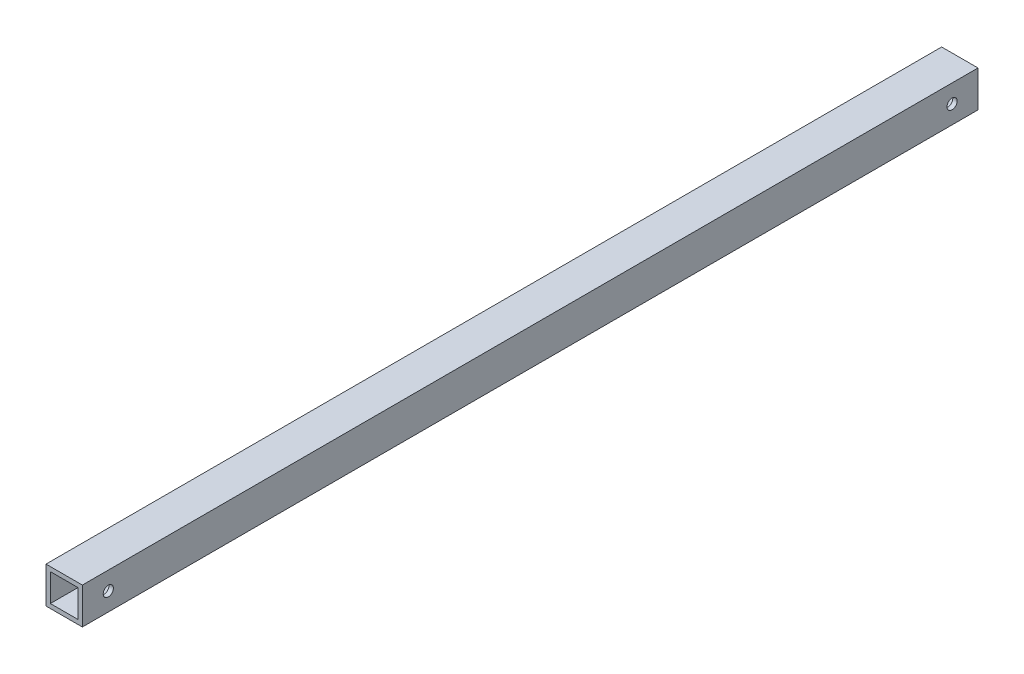
SolidWorks part; units mm, degrees
ref_plane "前视基准面" through (0, 0, 0) normal (0, 0, 1) x (1, 0, 0)
ref_plane "上视基准面" through (0, 0, 0) normal (0, 1, 0) x (1, 0, 0)
ref_plane "右视基准面" through (0, 0, 0) normal (1, 0, 0) x (0, 0, -1)
sketch "草图1" plane through (0, 0, 0) normal (0, 0, 1) x (1, 0, 0)
  line L1 (0, 0) -> (25, 0)
  line L2 (0, 0) -> (0, -25)
  line L3 (0, -25) -> (25, -25)
  line L4 (25, 0) -> (25, -25)
  line L5 (3, -3) -> (22, -3)
  line L6 (3, -3) -> (3, -22)
  line L7 (3, -22) -> (22, -22)
  line L8 (22, -3) -> (22, -22)
  dimension "D1" = 3
  dimension "D2" = 3
  dimension "D3" = 3
  dimension "D4" = 3
  dimension "D5" = 25
  dimension "D6" = 25
extrude "拉伸1" add sketch "草图1" along normal blind 616
hole_wizard "Ø7.0 (7) 直径孔1" positions "草图3" profile "草图4" hole size "Ø7.0" standard "GB" end condition through all
sketch "草图3" plane through (25, 0, 0) normal (1, 0, 0) x (0, 0, -1)
  line L0 (-616, -25) -> (-616, 0) construction
  line L1 (-616, -25) -> (0, -25) construction
  point P1 (-598.15, -12.5)
  dimension "D1" = 17.85
  dimension "D3" = 12.5
sketch "草图4" plane through (25, -12.5, 598.15) normal (0, 1, 0) x (0, 0, -1)
  line L0 (0, 0) -> (0, 25)
  line L1 (0, 25) -> (3.5, 25)
  line L2 (3.5, 25) -> (3.5, 0)
  line L5 (3.5, 0) -> (0, 0)
  line L11 (0, -6.35) -> (0, 107.95) construction
  dimension "通孔孔直径" = 7
  dimension "通孔孔深度" = 25
pattern_linear "阵列(线性)1" count 2 spacing 580.3 along (0, 0, -1) of "Ø7.0 (7) 直径孔1"
